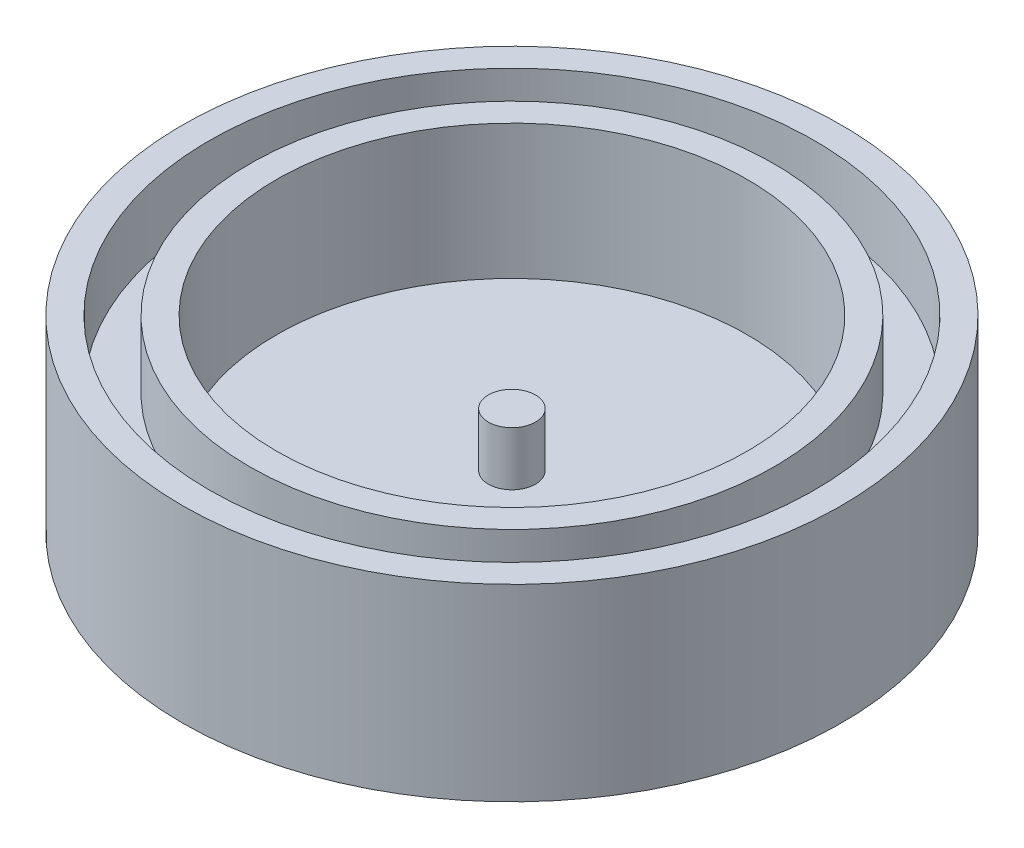
SolidWorks part; units mm, degrees
ref_plane "Front Plane" through (0, 0, 0) normal (0, 0, 1) x (1, 0, 0)
ref_plane "Top Plane" through (0, 0, 0) normal (0, 1, 0) x (1, 0, 0)
ref_plane "Right Plane" through (0, 0, 0) normal (1, 0, 0) x (0, 0, -1)
sketch "Sketch1" plane through (0, 0, 0) normal (0, 0, 1) x (1, 0, 0)
  line L0 (0, 0) -> (-24.5, 0)
  line L1 (-24.5, 0) -> (-24.5, 14)
  line L2 (-24.5, 14) -> (-22.5, 14)
  line L3 (-22.5, 14) -> (-22.5, 9)
  line L4 (-22.5, 9) -> (-19.5, 9)
  line L5 (-19.5, 9) -> (-19.5, 14)
  line L6 (-19.5, 14) -> (-17.5, 14)
  line L7 (-17.5, 14) -> (-17.5, 4)
  line L8 (-17.5, 4) -> (-1.75, 4)
  line L9 (-1.75, 4) -> (-1.75, 8)
  line L10 (-1.75, 8) -> (0, 8)
  line L11 (0, 8) -> (0, 0)
  dimension "D1" = 17.5
  dimension "D2" = 10
  dimension "D4" = 1.75
  dimension "D5" = 4
  dimension "D6" = 4
  dimension "D7" = 2
  dimension "D8" = 2
  dimension "D9" = 3
  dimension "D10" = 5
revolve "Revolve1" add sketch "Sketch1" angle 360 about L11
